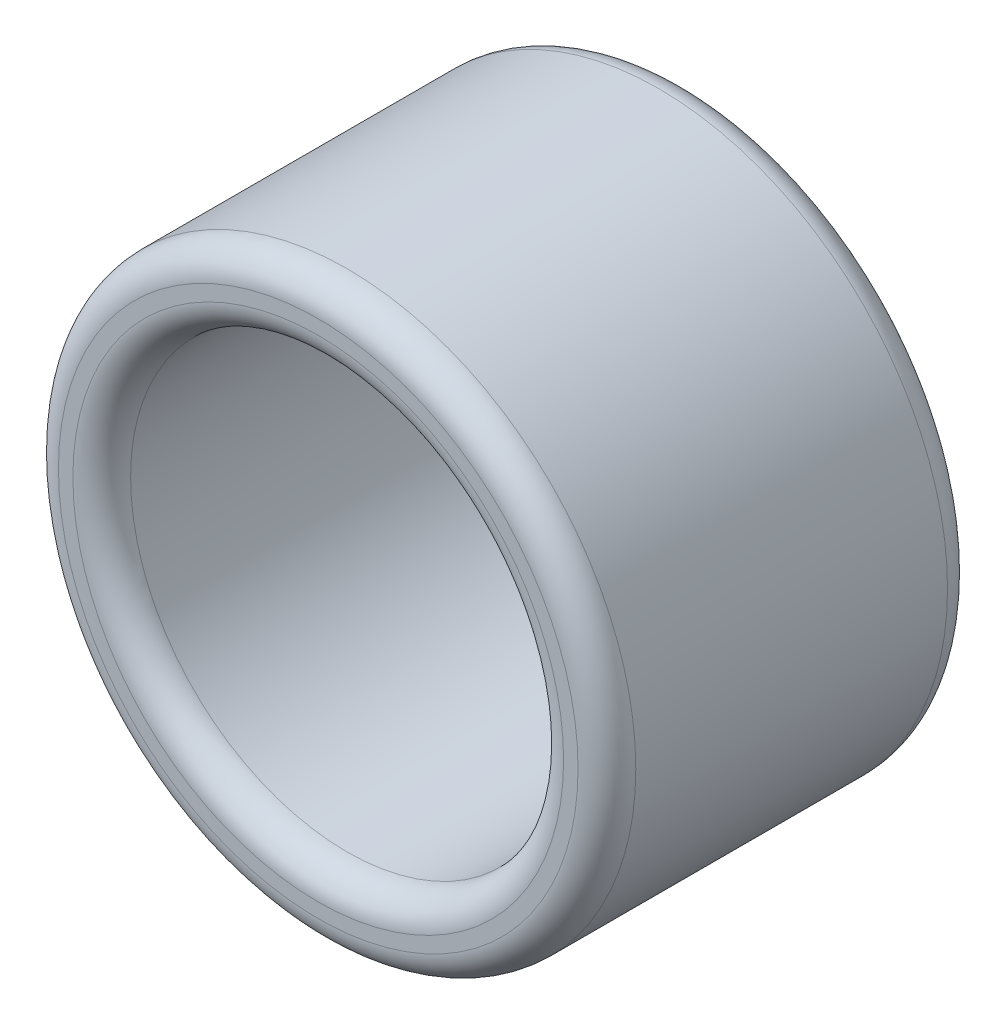
SolidWorks part; units mm, degrees
ref_plane "Plan de face" through (0, 0, 0) normal (0, 0, 1) x (1, 0, 0)
ref_plane "Plan de dessus" through (0, 0, 0) normal (0, 1, 0) x (1, 0, 0)
ref_plane "Plan de droite" through (0, 0, 0) normal (1, 0, 0) x (0, 0, -1)
sketch "Esquisse1" plane through (0, 0, 0) normal (0, 0, 1) x (1, 0, 0)
  circle A0 centre (0, 0) radius 2
  circle A1 centre (0, 0) radius 1.5
  dimension "D1" = 4
  dimension "D2" = 3
extrude "Boss.-Extru.1" add sketch "Esquisse1" along normal blind 2.56
fillet "Congé1" radius 0.2 4 edges at (1.5, 0, 0) (2, 0, 0) (1.5, 0, 2.56) (2, 0, 2.56)
